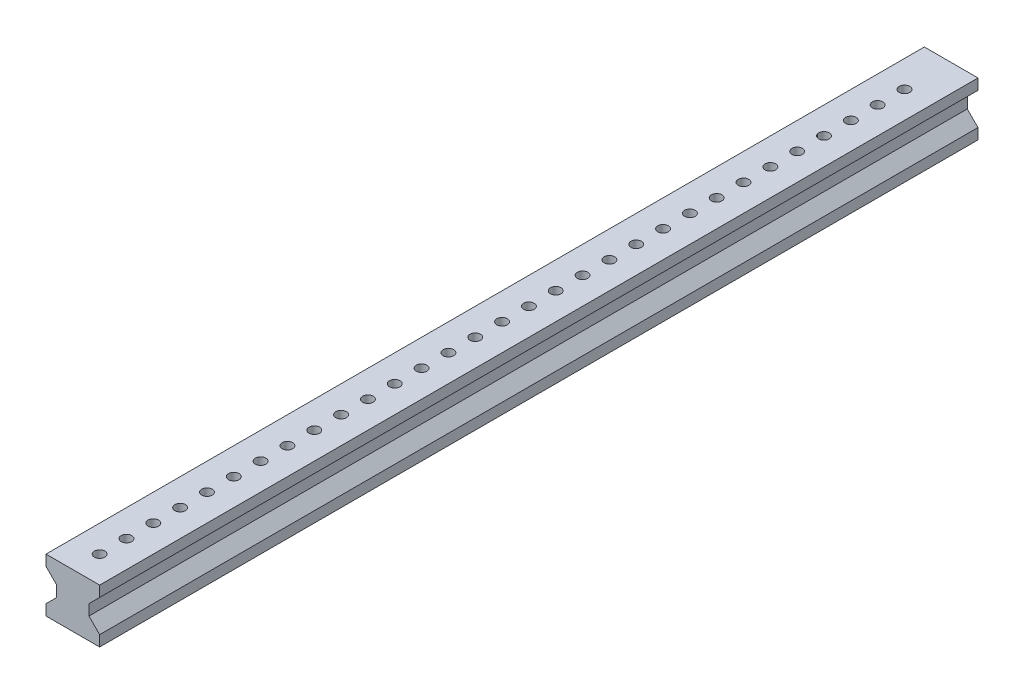
SolidWorks part; units mm, degrees
ref_plane "Front Plane" through (0, 0, 0) normal (0, 0, 1) x (1, 0, 0)
ref_plane "Top Plane" through (0, 0, 0) normal (0, 1, 0) x (1, 0, 0)
ref_plane "Right Plane" through (0, 0, 0) normal (1, 0, 0) x (0, 0, -1)
sketch "Sketch1" plane through (0, 0, 0) normal (0, 0, 1) x (1, 0, 0)
  line L0 (12.7, 12.7) -> (-12.7, 12.7)
  line L1 (-12.7, 12.7) -> (-12.7, 7.62)
  line L2 (-12.7, 7.62) -> (-7.62, 2.54)
  line L3 (-7.62, 2.54) -> (-7.62, -2.54)
  line L4 (-7.62, -2.54) -> (-12.7, -7.62)
  line L5 (-12.7, -7.62) -> (-12.7, -12.7)
  line L6 (-12.7, -12.7) -> (12.7, -12.7)
  line L7 (0, 0) -> (0, 22.2161) construction
  line L8 (12.7, -7.62) -> (12.7, -12.7)
  line L9 (7.62, -2.54) -> (12.7, -7.62)
  line L10 (7.62, 2.54) -> (7.62, -2.54)
  line L11 (12.7, 7.62) -> (7.62, 2.54)
  line L12 (12.7, 12.7) -> (12.7, 7.62)
  point P8 (-7.62, 0)
  point P13 (0, -12.7)
  point P18 (0, 12.7)
  dimension "D1" = 5.08
  dimension "D2" = 5.08
  dimension "D3" = 5.08
  dimension "D4" = 25.4
  dimension "D5" = 12.7
  dimension "D6" = 5.08
extrude "Boss-Extrude1" add sketch "Sketch1" along normal blind 415.798
sketch "Sketch3" plane through (0, 12.7, 0) normal (0, 1, 0) x (1, 0, 0)
  line L0 (12.7, -415.798) -> (-12.7, -415.798) construction
  line L1 (0, -415.798) -> (0, 13.5754) construction
  circle A0 centre (0, -403.098) radius 2.5
  circle A1 centre (0, -390.398) radius 2.5
  circle A2 centre (0, -377.698) radius 2.5
  circle A3 centre (0, -364.998) radius 2.5
  circle A4 centre (0, -352.298) radius 2.5
  circle A5 centre (0, -339.598) radius 2.5
  circle A6 centre (0, -326.898) radius 2.5
  circle A7 centre (0, -314.198) radius 2.5
  circle A8 centre (0, -301.498) radius 2.5
  circle A9 centre (0, -288.798) radius 2.5
  circle A10 centre (0, -276.098) radius 2.5
  circle A11 centre (0, -263.398) radius 2.5
  circle A12 centre (0, -250.698) radius 2.5
  circle A13 centre (0, -237.998) radius 2.5
  circle A14 centre (0, -225.298) radius 2.5
  circle A15 centre (0, -212.598) radius 2.5
  circle A16 centre (0, -199.898) radius 2.5
  circle A17 centre (0, -187.198) radius 2.5
  circle A18 centre (0, -174.498) radius 2.5
  circle A19 centre (0, -161.798) radius 2.5
  circle A20 centre (0, -149.098) radius 2.5
  circle A21 centre (0, -136.398) radius 2.5
  circle A22 centre (0, -123.698) radius 2.5
  circle A23 centre (0, -110.998) radius 2.5
  circle A24 centre (0, -98.298) radius 2.5
  circle A25 centre (0, -85.598) radius 2.5
  circle A26 centre (0, -72.898) radius 2.5
  arc A28 (0, -62.698) -> (0, -57.698) centre (0, -60.198) ccw [skipped]
  circle A29 centre (0, -60.198) radius 2.5
  circle A30 centre (0, -47.498) radius 2.5
  circle A31 centre (0, -34.798) radius 2.5
  circle A32 centre (0, -22.098) radius 2.5
  point P5 (0, -415.798)
  dimension "D1" = 5
  dimension "D2" = 12.7
  dimension "D3" = 28
  dimension "D4" = 3
  dimension "D5" = 3
extrude "Cut-Extrude1" cut sketch "Sketch3" against normal up to surface (25.4 mm away) up to face at (0, -12.7, 207.899)
